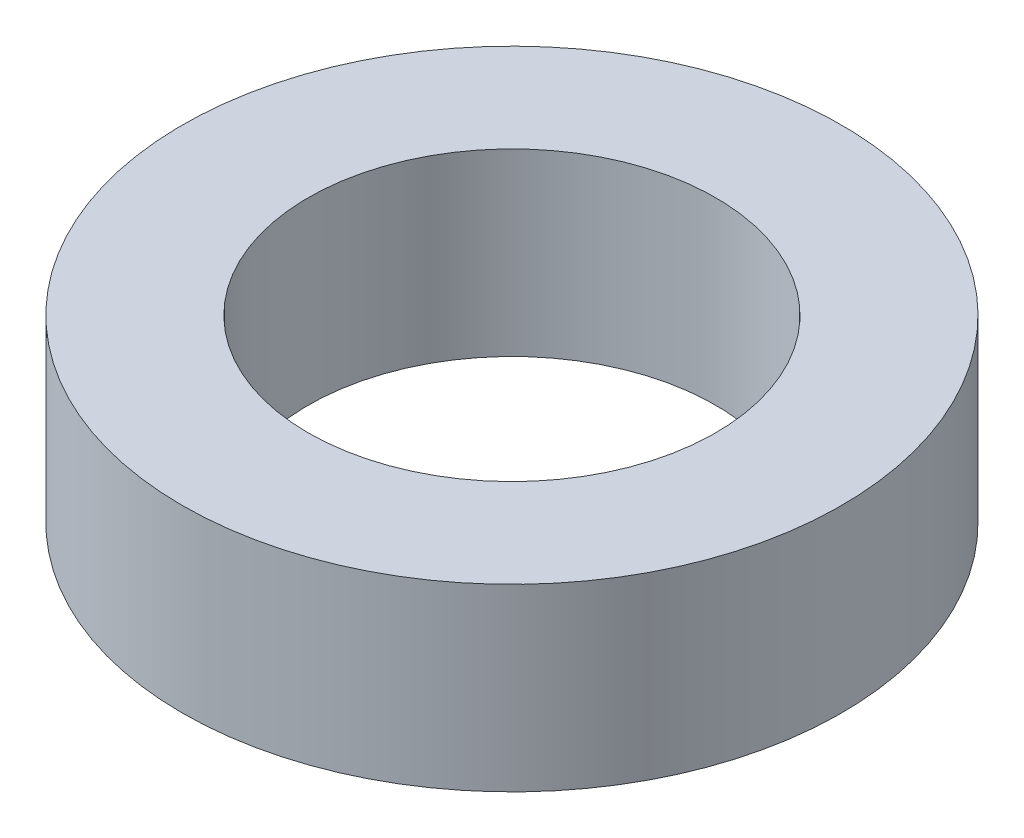
SolidWorks part; units mm, degrees
ref_plane "Front Plane" through (0, 0, 0) normal (0, 0, 1) x (1, 0, 0)
ref_plane "Top Plane" through (0, 0, 0) normal (0, 1, 0) x (1, 0, 0)
ref_plane "Right Plane" through (0, 0, 0) normal (1, 0, 0) x (0, 0, -1)
sketch "Sketch1" plane through (0, 0, 0) normal (0, 1, 0) x (1, 0, 0)
  circle A0 centre (0, 0) radius 1.7
  circle A1 centre (0, 0) radius 2.75
  point P3 (0, 0)
  dimension "D1" = 3.4
  dimension "D2" = 5.5
extrude "Boss-Extrude1" add sketch "Sketch1" along normal blind 1.5
